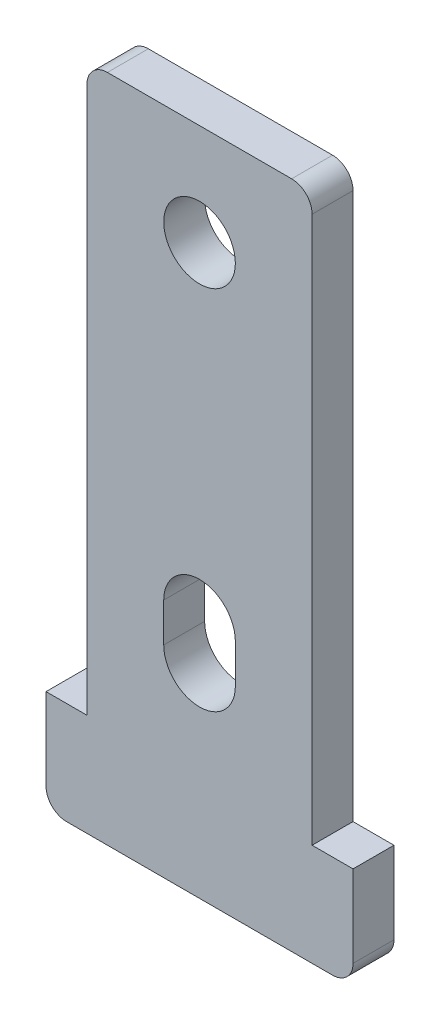
SolidWorks part; units mm, degrees
ref_plane "Ön Düzlem" through (0, 0, 0) normal (0, 0, 1) x (1, 0, 0)
ref_plane "Üst Düzlem" through (0, 0, 0) normal (0, 1, 0) x (1, 0, 0)
ref_plane "Sağ Düzlem" through (0, 0, 0) normal (1, 0, 0) x (0, 0, -1)
sketch "Çizim1" plane through (0, 0, 0) normal (0, 0, 1) x (1, 0, 0)
  line L6 (-4.4595, -15.6757) -> (-6.4595, -15.6757)
  line L7 (-6.4595, -15.6757) -> (-6.4595, -19.6757)
  line L8 (-5.4595, -20.6757) -> (7.5405, -20.6757)
  line L9 (6.5405, -15.6757) -> (6.5405, 11.0243)
  line L10 (-4.4595, -15.6757) -> (-4.4595, 11.0243)
  line L11 (8.5405, -19.6757) -> (8.5405, -15.6757)
  line L12 (8.5405, -15.6757) -> (6.5405, -15.6757)
  line L13 (1.0405, -20.6757) -> (1.0405, -12.5757)
  line L16 (1.0405, -20.6757) -> (1.0405, -12.5757)
  line L17 (-4.4595, -15.6757) -> (-4.4595, -20.6757)
  line L19 (-0.7095, -10.8257) -> (-0.7095, -8.9257)
  line L21 (2.7905, -10.8257) -> (2.7905, -8.9257)
  line L22 (-3.4595, 12.0243) -> (5.5405, 12.0243)
  line L24 (6.5405, -15.6757) -> (6.5405, -20.6757)
  arc A0 (-6.4595, -19.6757) -> (-5.4595, -20.6757) centre (-5.4595, -19.6757) ccw
  arc A1 (7.5405, -20.6757) -> (8.5405, -19.6757) centre (7.5405, -19.6757) ccw
  circle A4 centre (1.0405, 7.0743) radius 1.75
  arc A6 (5.5405, 12.0243) -> (6.5405, 11.0243) centre (5.5405, 11.0243) cw
  arc A7 (-4.4595, 11.0243) -> (-3.4595, 12.0243) centre (-3.4595, 11.0243) cw
  arc A8 (2.7905, -8.9257) -> (-0.7095, -8.9257) centre (1.0405, -8.9257) ccw
  arc A9 (-0.7095, -10.8257) -> (2.7905, -10.8257) centre (1.0405, -10.8257) ccw
  point P0 (0, 0)
  point P25 (1.0405, -7.8757)
  dimension "D2" = 5
  dimension "D3" = 5
extrude "Yükseklik-Ekstrüzyon1" add sketch "Çizim1" along normal blind 2
